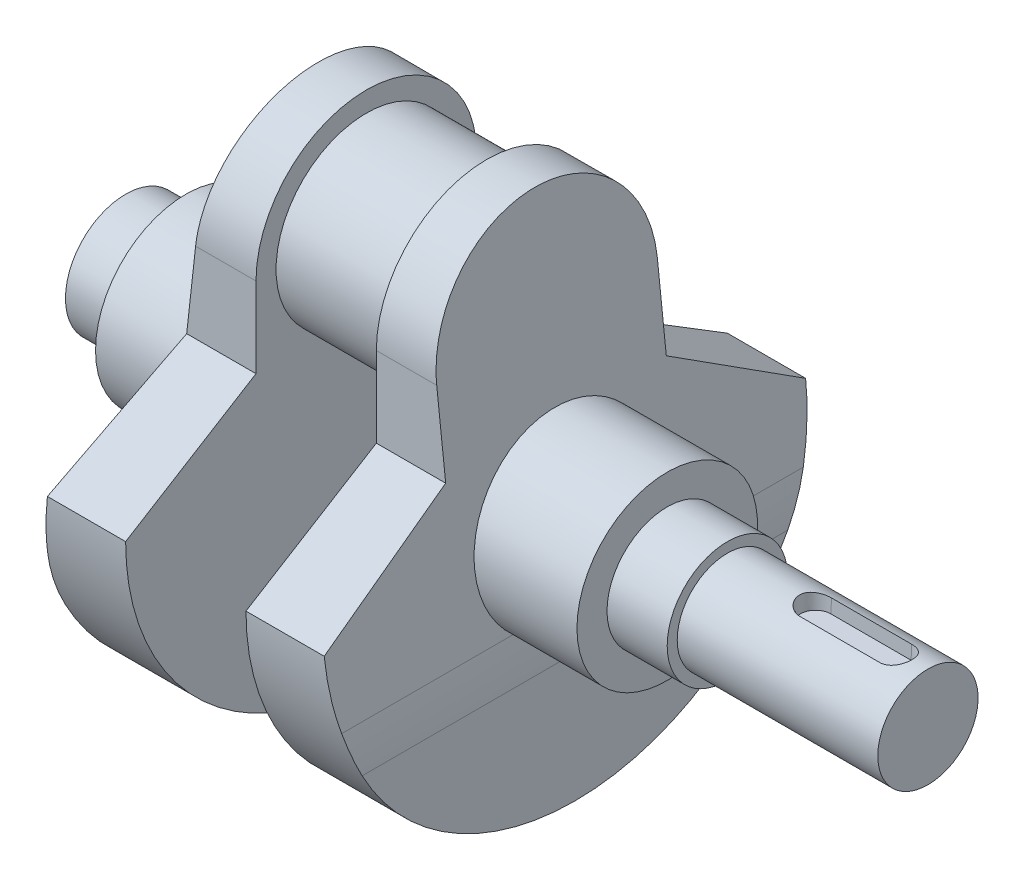
SolidWorks part; units mm, degrees
material "Commercially Pure CP-Ti UNS R50400 (SS)"
ref_plane "Front Plane" through (0, 0, 0) normal (0, 0, 1) x (1, 0, 0)
ref_plane "Top Plane" through (0, 0, 0) normal (0, 1, 0) x (1, 0, 0)
ref_plane "Right Plane" through (0, 0, 0) normal (1, 0, 0) x (0, 0, -1)
sketch "Sketch2" plane through (0, 0, 0) normal (1, 0, 0) x (0, 0, -1)
  circle A0 centre (0, 0) radius 22.5
  dimension "D1" = 45
extrude "Boss-Extrude1" add sketch "Sketch2" along normal blind 15
sketch "Sketch3" plane through (0, 0, 0) normal (1, 0, 0) x (0, 0, -1)
  line L0 (-27.5, 0) -> (-27.5, -20)
  line L1 (-27.5, -20) -> (-60, -40)
  line L2 (0, 0) -> (0, -40) construction
  line L3 (27.5, -20) -> (60, -40)
  line L4 (27.5, 0) -> (27.5, -20)
  arc A0 (27.5, 0) -> (-27.5, 0) centre (0, 0) ccw
  arc A1 (-60, -40) -> (60, -40) centre (0, -40) ccw
  point P12 (0, 0)
  point P13 (0, 0)
  dimension "D1" = 120
  dimension "D2" = 55
  dimension "D3" = 40
  dimension "D4" = 20
extrude "Boss-Extrude2" add sketch "Sketch3" against normal blind 22
sketch "Sketch4" plane through (0, 0, 0) normal (0, 0, 1) x (1, 0, 0)
  line L0 (-12, 27.5) -> (-22, 27.5)
  line L1 (0, 27.5) -> (-22, 27.5) construction
  line L2 (-22, 27.5) -> (-22, -62.5)
  line L3 (-22, -40) -> (-22, -100) construction
  line L4 (-22, -62.5) -> (-12, 27.5)
  dimension "D1" = 10
  dimension "D2" = 90
extrude "Cut-Extrude2" cut sketch "Sketch4" against normal through all both and the other way through all
fillet "Fillet1" radius 100 1 edges at (-22, -62.5, 0)
sketch "Sketch6" plane through (0, 0, 0) normal (0, 0, 1) x (1, 0, 0)
  line L0 (-22, -100) -> (-22, 0) construction
  line L1 (-22, 0) -> (15, 0) construction
  line L2 (15, -22.5) -> (15, 22.5) construction
  line L3 (-17, -17.5) -> (-45, -17.5)
  line L4 (-45, -17.5) -> (-45, -25)
  line L5 (-45, -25) -> (-60, -25)
  line L6 (-60, -25) -> (-60, -27.5)
  line L7 (-60, -27.5) -> (-110, -27.5)
  line L8 (-110, -27.5) -> (-110, -40)
  line L9 (-110, -40) -> (-17, -40)
  line L10 (-17, -40) -> (-17, -17.5)
  line L13 (0, -40) -> (37.0725, -40) construction
  line L14 (-15.0556, 0) -> (-17.2778, -20) construction
  point P8 (0, 0)
  dimension "D1" = 40
  dimension "D2" = 45
  dimension "D3" = 30
  dimension "D4" = 25
  dimension "D5" = 60
  dimension "D6" = 50
  dimension "D7" = 15
revolve "Revolve1" add sketch "Sketch6" angle 360 about L13
sketch "Sketch7" plane through (0, 0, 0) normal (0, 0, 1) x (1, 0, 0)
  line L3 (-60, -40) -> (-110, -40) construction
  line L4 (-60, -27.5) -> (-60, -52.5) construction
  line L5 (-110, -27.5) -> (-110, -52.5) construction
sketch "Sketch8" plane through (0, 0, 0) normal (0, 1, 0) x (1, 0, 0)
  line L0 (-82, 0) -> (-102, 0) construction
  line L1 (-60, 0) -> (-110, 0) construction
  line L2 (-82, -4) -> (-102, -4)
  line L3 (-82, 4) -> (-102, 4)
  line L4 (-110, 12.5) -> (-110, -12.5) construction
  arc A0 (-82, -4) -> (-82, 4) centre (-82, 0) ccw
  arc A1 (-102, 4) -> (-102, -4) centre (-102, 0) ccw
  point P4 (-92, 0)
  dimension "D1" = 4
  dimension "D2" = 20
  dimension "D3" = 8
extrude "Cut-Extrude3" cut sketch "Sketch8" against normal blind 4 draft 3 from offset 27.5 offset against normal yes
mirror "Mirror2" about plane through (15, 0, 0) normal (1, 0, 0) of bodies 106
sketch "Sketch9" plane through (0, 0, 0) normal (0, 0, 1) x (1, 0, 0)
  line L0 (-60, 19.972) -> (-60, -84.9519)
  line L1 (-60, -25) -> (-60, -55) construction
  line L7 (-120.2342, 24.2343) -> (-60, 24.2343)
  line L8 (-120.2342, 24.2343) -> (-120.2342, -63.7442)
  line L9 (-120.2342, -63.7442) -> (-60, -63.7442)
  line L10 (-60, 24.2343) -> (-60, -63.7442)
extrude "Cut-Extrude7" cut sketch "Sketch9" against normal through all both and the other way through all contours L10 L7 L8 L9 L0
